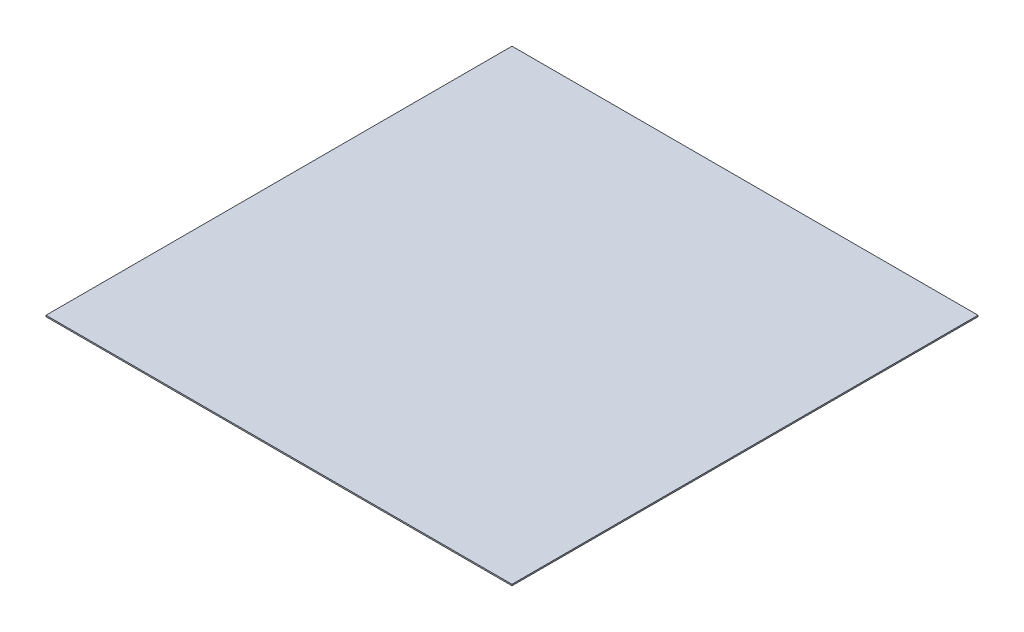
SolidWorks part; units mm, degrees
ref_plane "前视基准面" through (0, 0, 0) normal (0, 0, 1) x (1, 0, 0)
ref_plane "上视基准面" through (0, 0, 0) normal (0, 1, 0) x (1, 0, 0)
ref_plane "右视基准面" through (0, 0, 0) normal (1, 0, 0) x (0, 0, -1)
other "Configuration Table"
sketch "草图1" plane through (0, 0, 0) normal (0, 1, 0) x (1, 0, 0)
  line L1 (0, 0) -> (345, 0)
  line L2 (0, 0) -> (0, -345)
  line L3 (0, -345) -> (345, -345)
  line L4 (345, 0) -> (345, -345)
  dimension "D1" = 345
  dimension "D2" = 345
extrude "凸台-拉伸1" add sketch "草图1" along normal blind 1 contours L2 L1 L4 L3
